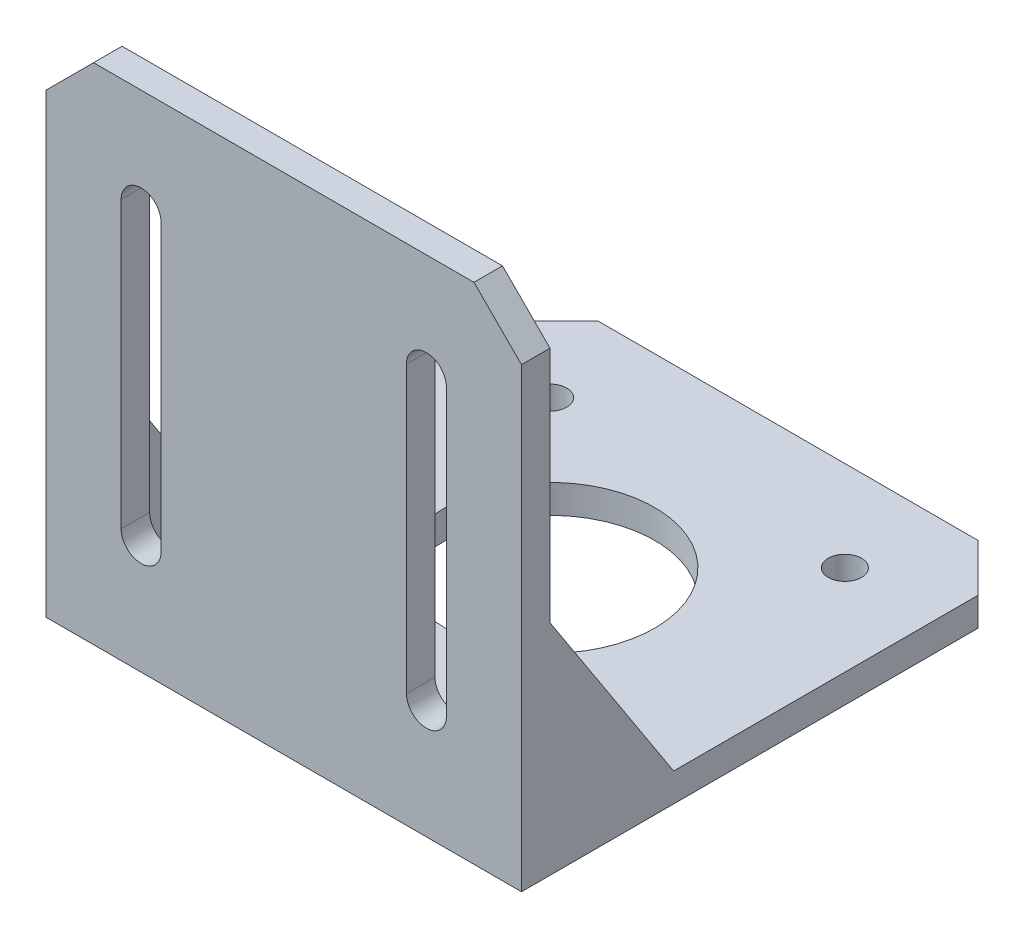
SolidWorks part; units mm, degrees
ref_plane "前视基准面" through (0, 0, 0) normal (0, 0, 1) x (1, 0, 0)
ref_plane "上视基准面" through (0, 0, 0) normal (0, 1, 0) x (1, 0, 0)
ref_plane "右视基准面" through (0, 0, 0) normal (1, 0, 0) x (0, 0, -1)
other "Configuration Table"
sketch "草图1" plane through (0, 0, 0) normal (0, 1, 0) x (1, 0, 0)
  line L0 (25, 50) -> (25, 0) construction
  line L1 (0, 0) -> (50, 0)
  line L2 (0, 0) -> (0, 45)
  line L3 (5, 50) -> (45, 50)
  line L4 (50, 0) -> (50, 45)
  line L5 (0, 25) -> (50, 25) construction
  line L6 (0, 45) -> (5, 50)
  line L7 (45, 50) -> (50, 45)
  circle A0 centre (25, 25) radius 11
  circle A1 centre (9.5, 40.5) radius 1.75
  circle A2 centre (40.5, 40.5) radius 1.75
  circle A3 centre (40.5, 9.5) radius 1.75
  circle A4 centre (9.5, 9.5) radius 1.75
  point P1 (50, 50)
  point P2 (0, 50)
  dimension "D3" = 22
  dimension "D4" = 15.5
  dimension "D1" = 50
  dimension "D2" = 50
  dimension "D5" = 15.5
extrude "凸台-拉伸1" add sketch "草图1" along normal blind 3
sketch "草图2" plane through (0, 0, 0) normal (0, 0, 1) x (1, 0, 0)
  line L0 (25, 53) -> (25, 0) construction
  line L1 (0, 0) -> (50, 0)
  line L2 (0, 0) -> (0, 48)
  line L3 (5, 53) -> (45, 53)
  line L4 (50, 0) -> (50, 48)
  line L6 (7.9, 42) -> (7.9, 12)
  line L8 (12.1, 42) -> (12.1, 12)
  line L13 (37.9, 42) -> (37.9, 12)
  line L14 (42.1, 42) -> (42.1, 12)
  line L15 (0, 48) -> (5, 53)
  line L16 (45, 53) -> (50, 48)
  arc A0 (7.9, 42) -> (12.1, 42) centre (10, 42) cw
  arc A1 (7.9, 12) -> (12.1, 12) centre (10, 12) ccw
  arc A2 (42.1, 12) -> (37.9, 12) centre (40, 12) cw
  arc A3 (42.1, 42) -> (37.9, 42) centre (40, 42) ccw
  point P1 (50, 53)
  point P2 (0, 53)
  dimension "D1" = 53
  dimension "D2" = 50
  dimension "D3" = 30
  dimension "D4" = 4.2
  dimension "D5" = 10
extrude "凸台-拉伸2" add sketch "草图2" along normal blind 3
sketch "草图3" plane through (0, 0, 0) normal (-1, 0, 0) x (0, 0, 1)
  line L0 (0, 3) -> (-13, 3)
  line L1 (-45, 3) -> (0, 3) construction
  line L2 (-13, 3) -> (0, 23)
  line L3 (0, 48) -> (0, 3) construction
  line L4 (0, 23) -> (0, 3)
  dimension "D1" = 13
  dimension "D2" = 20
extrude "凸台-拉伸3" add sketch "草图3" against normal blind 3
sketch "草图4" plane through (50, 0, 0) normal (1, 0, 0) x (0, 0, -1)
  line L0 (0, 3) -> (13, 3)
  line L1 (0, 3) -> (45, 3) construction
  line L2 (13, 3) -> (0, 23)
  line L3 (0, 3) -> (0, 48) construction
  line L4 (0, 23) -> (0, 3)
  dimension "D1" = 20
  dimension "D2" = 13
extrude "凸台-拉伸4" add sketch "草图4" against normal blind 3
